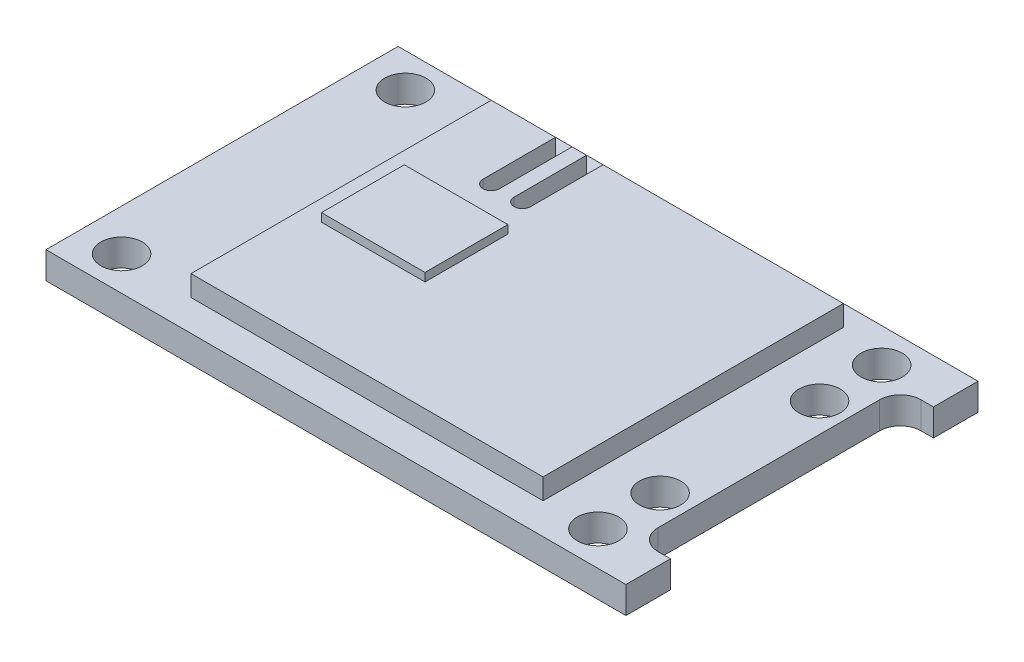
SolidWorks part; units mm, degrees
ref_plane "Спереди" through (0, 0, 0) normal (0, 0, 1) x (1, 0, 0)
ref_plane "Сверху" through (0, 0, 0) normal (0, 1, 0) x (1, 0, 0)
ref_plane "Справа" through (0, 0, 0) normal (1, 0, 0) x (0, 0, -1)
sketch "Эскиз1" plane through (0, 0, 0) normal (0, 1, 0) x (1, 0, 0)
  line L0 (12.4, 5.35) -> (12.4, -5.35)
  line L1 (-14, 8.5) -> (14, 8.5)
  line L2 (-14, 8.5) -> (-14, -8.5)
  line L3 (-14, -8.5) -> (14, -8.5)
  line L4 (14, 8.5) -> (14, 6.35)
  line L5 (-14, 8.5) -> (14, -8.5) construction
  line L6 (-14, -8.5) -> (14, 8.5) construction
  line L7 (13.4, 6.35) -> (14, 6.35)
  line L8 (13.4, -6.35) -> (14, -6.35)
  line L9 (14, -6.35) -> (14, -8.5)
  arc A0 (13.4, 6.35) -> (12.4, 5.35) centre (13.4, 5.35) ccw
  arc A1 (12.4, -5.35) -> (13.4, -6.35) centre (13.4, -5.35) ccw
  point P0 (0, 0)
  point P9 (13.9472, 7.2448)
  point P16 (11.9009, -5.4511)
  point P17 (12.4, 0)
  point P18 (11.8598, 6.1272)
  point P19 (10.4515, -5.0746)
  point P20 (14.472, 7.484)
  point P21 (14.3269, 8.4177)
  point P22 (14.0844, 8.4791)
  dimension "D3" = 1
  dimension "D1" = 28
  dimension "D2" = 17
  dimension "D4" = 1.6
  dimension "D5" = 12.7
extrude "Бобышка-Вытянуть1" add sketch "Эскиз1" along normal blind 1.3
sketch "Эскиз2" plane through (0, 1.3, 0) normal (0, 1, 0) x (1, 0, 0)
  line L0 (11, 6.85) -> (11, -6.85) construction
  line L1 (11, 3.85) -> (11, -3.85) construction
  line L2 (-12, -6.85) -> (-12, 6.85) construction
  line L3 (-14, 8.5) -> (-14, -8.5) construction
  line L4 (14, 6.35) -> (14, 8.5) construction
  circle A1 centre (11, 6.85) radius 1
  circle A2 centre (-12, 6.85) radius 1
  circle A3 centre (-12, -6.85) radius 1
  circle A4 centre (11, -6.85) radius 1
  circle A5 centre (11, -3.85) radius 1
  circle A6 centre (11, 3.85) radius 1
  point P0 (-11.1245, -6.4382)
  point P4 (7.5623, -7.0513)
  point P6 (7.5915, -3.9855)
  point P8 (7.5623, 7.0513)
  point P12 (0, 0)
  point P15 (11, 0)
  point P18 (11, 0)
  point P21 (-12, 0)
  dimension "D3" = 2
  dimension "D1" = 13.7
  dimension "D2" = 3
  dimension "D4" = 2
  dimension "D5" = 3
extrude "Вырез-Вытянуть1" cut sketch "Эскиз2" against normal through all
sketch "Эскиз3" plane through (0, 1.3, 0) normal (0, 1, 0) x (1, 0, 0)
  line L0 (-5.4, 4) -> (-5.4, 7.5)
  line L1 (-8.5, 7.5) -> (-5.4, 7.5)
  line L2 (-8.5, 7.5) -> (-8.5, -7)
  line L3 (-8.5, -7) -> (8.5, -7)
  line L4 (8.5, 7.5) -> (8.5, -7)
  line L5 (-8.5, 7.5) -> (8.5, -7) construction
  line L6 (-8.5, -7) -> (8.5, 7.5) construction
  line L7 (-3.1, 7.5) -> (8.5, 7.5)
  line L8 (-3.1, 4) -> (-3.1, 7.5)
  line L9 (-3.9, 4) -> (-3.9, 7.5)
  line L10 (-4.6, 4) -> (-4.6, 7.5)
  line L11 (-4.6, 7.5) -> (-3.9, 7.5)
  line L12 (-14, 8.5) -> (-14, -8.5) construction
  line L13 (14, 6.35) -> (14, 8.5) construction
  line L14 (14, 8.5) -> (-14, 8.5) construction
  line L15 (-14, -8.5) -> (14, -8.5) construction
  arc A0 (-5.4, 4) -> (-4.6, 4) centre (-5, 4) ccw
  arc A1 (-3.9, 4) -> (-3.1, 4) centre (-3.5, 4) ccw
  point P0 (0, 0.25)
  point P8 (-0.6784, 4.7847)
  point P11 (0, 0)
  point P12 (-0.409, 7.2647)
  point P19 (2.4751, 7.2092)
  point P23 (0, 0)
  point P25 (0, 0)
  point P26 (-3.9, 7.0439)
  dimension "D5" = 0.4
  dimension "D1" = 5.5
  dimension "D2" = 5.5
  dimension "D3" = 9
  dimension "D4" = 10.5
  dimension "D6" = 4.5
  dimension "D7" = 1.5
  dimension "D8" = 1
extrude "Бобышка-Вытянуть2" add sketch "Эскиз3" along normal blind 1
sketch "Эскиз4" plane through (0, 2.3, 0) normal (0, 1, 0) x (1, 0, 0)
  line L1 (-7.5, 2.3) -> (-2.5, 2.3)
  line L2 (-7.5, 2.3) -> (-7.5, -1.7)
  line L3 (-7.5, -1.7) -> (-2.5, -1.7)
  line L4 (-2.5, 2.3) -> (-2.5, -1.7)
  line L5 (-7.5, 2.3) -> (-2.5, -1.7) construction
  line L6 (-7.5, -1.7) -> (-2.5, 2.3) construction
  line L7 (14, 8.5) -> (-14, 8.5) construction
  line L8 (-14, 8.5) -> (-14, -8.5) construction
  point P0 (-5, 0.3)
  dimension "D1" = 5
  dimension "D2" = 8.2
  dimension "D3" = 4
  dimension "D4" = 9
extrude "Бобышка-Вытянуть3" add sketch "Эскиз4" along normal blind 0.4
